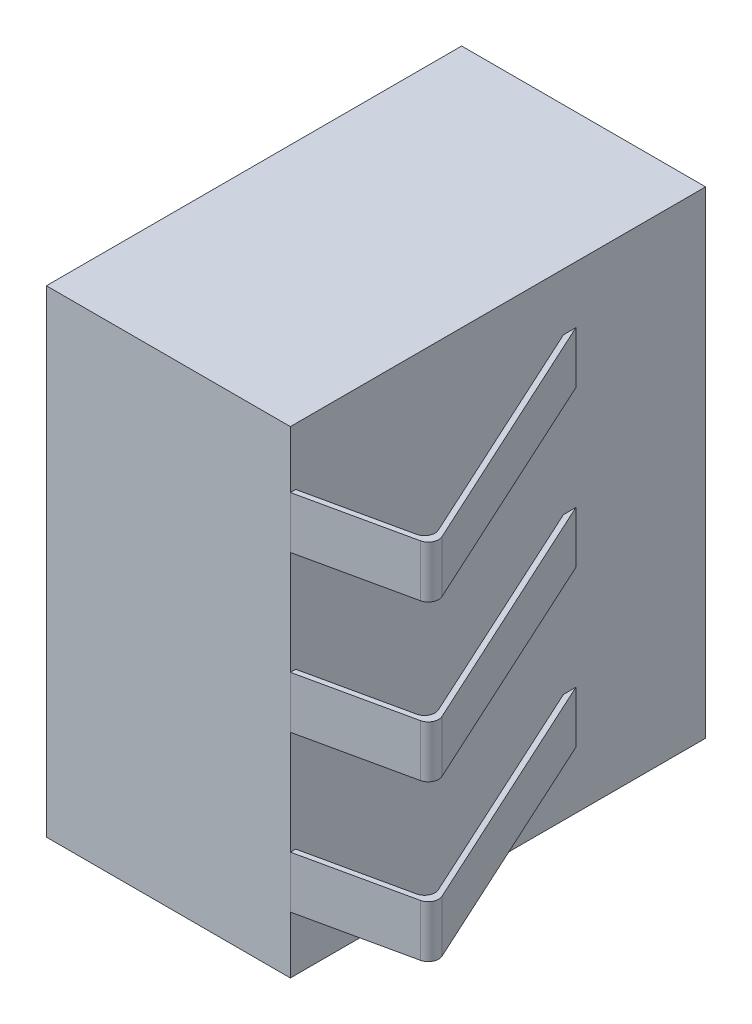
SolidWorks part; units mm, degrees
ref_plane "Front Plane" through (0, 0, 0) normal (0, 0, 1) x (1, 0, 0)
ref_plane "Top Plane" through (0, 0, 0) normal (0, 1, 0) x (1, 0, 0)
ref_plane "Right Plane" through (0, 0, 0) normal (1, 0, 0) x (0, 0, -1)
sketch "Sketch1" plane through (0, 0, 0) normal (0, 0, 1) x (1, 0, 0)
  line L1 (-2.35, -4.6) -> (2.35, -4.6)
  line L2 (-2.35, -4.6) -> (-2.35, 4.6)
  line L3 (-2.35, 4.6) -> (2.35, 4.6)
  line L4 (2.35, -4.6) -> (2.35, 4.6)
  line L5 (-2.35, -4.6) -> (2.35, 4.6) construction
  line L6 (-2.35, 4.6) -> (2.35, -4.6) construction
  point P0 (0, 0)
  dimension "D1" = 4.7
  dimension "D2" = 9.2
extrude "Boss-Extrude1" add sketch "Sketch1" along normal blind 8
sketch "Sketch2" plane through (0, 0, 0) normal (0, 1, 0) x (1, 0, 0)
  line L0 (2.35, -8) -> (4.65, -7.5)
  line L1 (2.35, -8) -> (2.35, 0) construction
  line L2 (4.65, -7.5) -> (2.35, -2.5)
  line L3 (2.35, -2.5) -> (2.35, -2.7393)
  line L4 (2.35, -2.7393) -> (4.5071, -7.4287)
  line L5 (4.5071, -7.4287) -> (2.35, -7.8977)
  line L6 (2.35, -7.8977) -> (2.35, -8)
  line L7 (4.5071, -7.4287) -> (4.598, -7.3869) construction
  line L8 (4.5071, -7.4287) -> (4.5284, -7.5264) construction
  line L10 (2.35, 0) -> (-2.35, 0) construction
  line L11 (-2.35, -8) -> (-2.35, 0) construction
  line L12 (2.35, -8) -> (-2.35, -8) construction
  dimension "D1" = 0.1
  dimension "D2" = 2.5
  dimension "D3" = 7
  dimension "D4" = 0.5
extrude "Boss-Extrude2" add sketch "Sketch2" along normal mid plane 1
fillet "Fillet1" radius 0.2 1 edges at (4.5071, 0, 7.4287)
fillet "Fillet2" radius 0.2 1 edges at (4.65, 0, 7.5)
pattern_linear "LPattern2" count 2 spacing 3 along (0, -1, 0) count 2 spacing 3 along (0, 1, 0) of "Boss-Extrude2", "Fillet1", "Fillet2"
